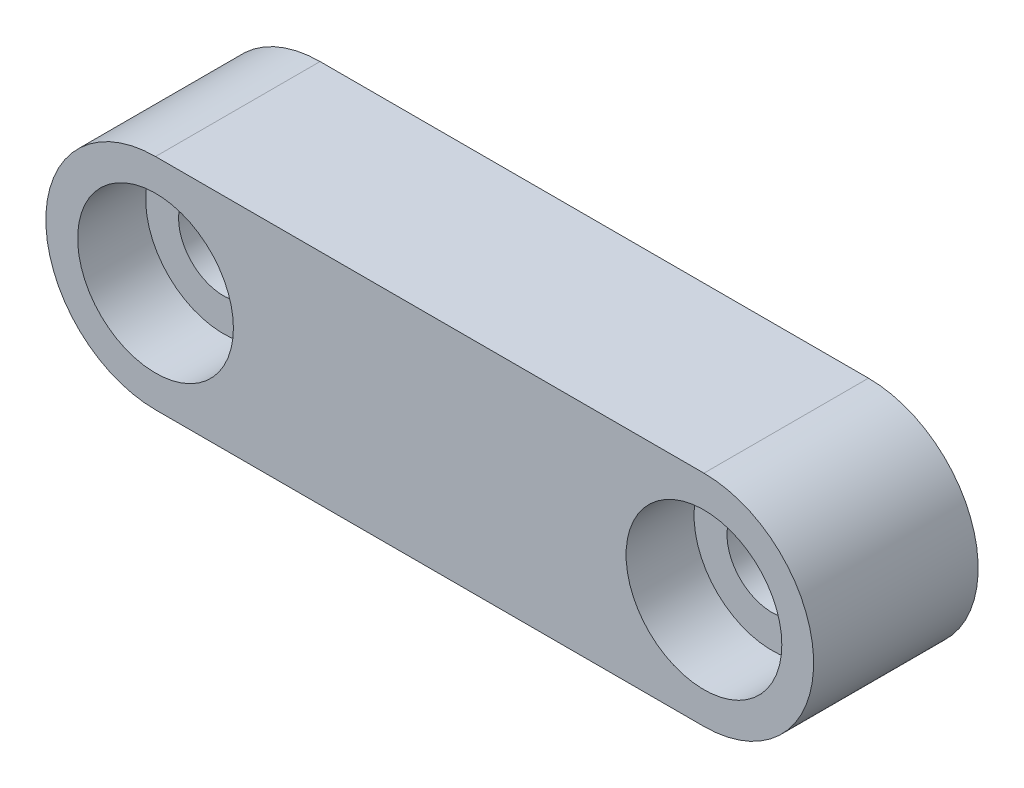
SolidWorks part; units mm, degrees
material "ABS"
ref_plane "前基準面" through (0, 0, 0) normal (0, 0, 1) x (1, 0, 0)
ref_plane "上基準面" through (0, 0, 0) normal (0, 1, 0) x (1, 0, 0)
ref_plane "右基準面" through (0, 0, 0) normal (1, 0, 0) x (0, 0, -1)
sketch "草圖1" plane through (0, 0, 0) normal (0, 0, 1) x (1, 0, 0)
  line L0 (-12.5, 0) -> (12.5, 0) construction
  line L1 (-12.5, 5) -> (12.5, 5)
  line L2 (-12.5, -5) -> (12.5, -5)
  arc A0 (-12.5, 5) -> (-12.5, -5) centre (-12.5, 0) ccw
  arc A1 (12.5, -5) -> (12.5, 5) centre (12.5, 0) ccw
  circle A2 centre (-12.5, 0) radius 2.05
  circle A3 centre (12.5, 0) radius 2.05
  point P3 (0, 0)
  dimension "D1" = 5
  dimension "D3" = 4.1
  dimension "D2" = 25
extrude "填料-伸長1" add sketch "草圖1" along normal blind 7.5
sketch "草圖2" plane through (0, 0, 7.5) normal (0, 0, 1) x (1, 0, 0)
  line L0 (0, 0) -> (0, 4.2786) construction
  circle A0 centre (12.5, 0) radius 3.55
  circle A1 centre (-12.5, 0) radius 3.55
  circle A2 centre (-12.5, 0) radius 2.05 construction
  dimension "D1" = 7.1
extrude "除料-伸長1" cut sketch "草圖2" against normal blind 3.1
